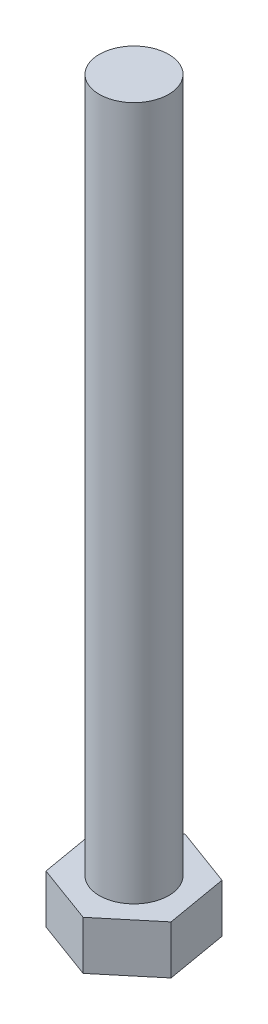
SolidWorks part; units mm, degrees
ref_plane "Спереди" through (0, 0, 0) normal (0, 0, 1) x (1, 0, 0)
ref_plane "Сверху" through (0, 0, 0) normal (0, 1, 0) x (1, 0, 0)
ref_plane "Справа" through (0, 0, 0) normal (1, 0, 0) x (0, 0, -1)
sketch "Эскиз1" plane through (0, 0, 0) normal (0, 1, 0) x (1, 0, 0)
  line L1 (4.2233, -1.5536) -> (3.4571, 2.8807)
  line L2 (3.4571, 2.8807) -> (-0.7661, 4.4343)
  line L3 (-0.7661, 4.4343) -> (-4.2233, 1.5536)
  line L4 (-4.2233, 1.5536) -> (-3.4571, -2.8807)
  line L5 (-3.4571, -2.8807) -> (0.7661, -4.4343)
  line L6 (0.7661, -4.4343) -> (4.2233, -1.5536)
  circle A0 centre (0, 0) radius 4.5 construction
  circle A1 centre (0, 0) radius 3.8971 construction
  dimension "D1" = 9
extrude "Вытянуть1" add sketch "Эскиз1" along normal blind 3.5
sketch "Эскиз2" plane through (0, 3.5, 0) normal (0, 1, 0) x (1, 0, 0)
  circle A0 centre (0, 0) radius 2.5
  dimension "D1" = 5
extrude "Вытянуть2" add sketch "Эскиз2" along normal blind 50
